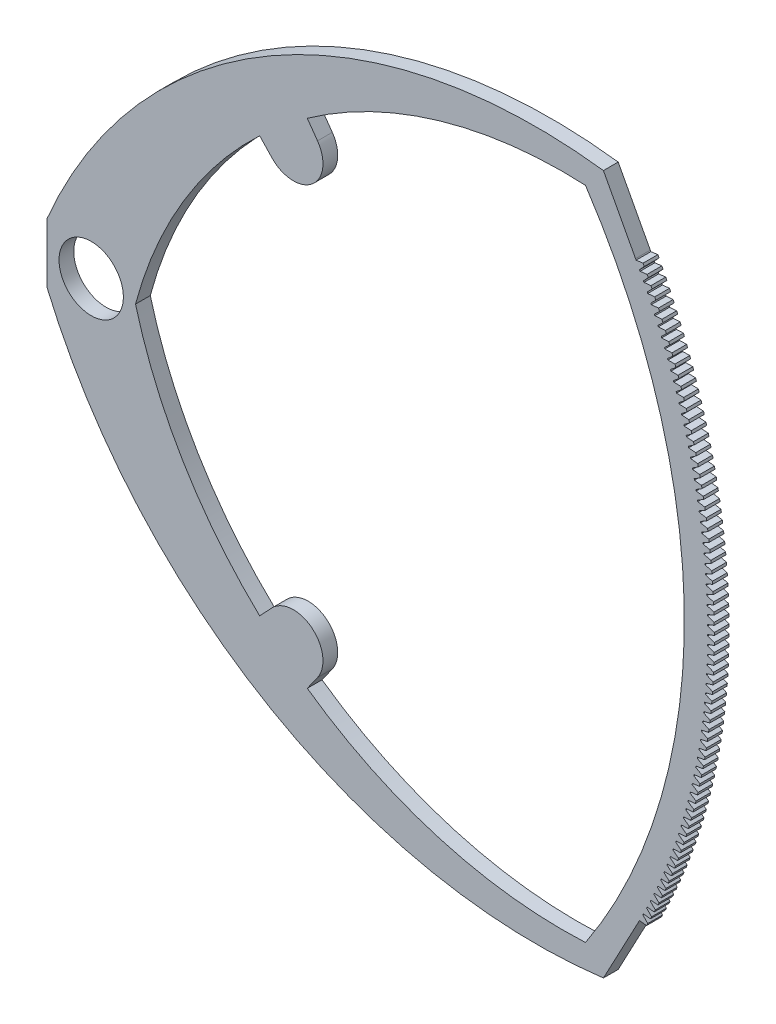
SolidWorks part; units mm, degrees
ref_plane "Plane1" through (0, 0, 0) normal (0, 0, 1) x (1, 0, 0)
ref_plane "Plane2" through (0, 0, 0) normal (0, 1, 0) x (1, 0, 0)
ref_plane "Plane3" through (0, 0, 0) normal (1, 0, 0) x (0, 0, -1)
sketch "Sketch3" plane through (0, 0, 0) normal (0, 0, 1) x (1, 0, 0)
  line L0 (0, 0) -> (305.6191, 0) construction
  line L2 (178.8854, 110) -> (173.446, 118.3912) construction
  line L5 (-15, -10) -> (-15, 10)
  line L12 (57.0436, 70.3911) -> (61.1578, 66.0237)
  line L13 (61.1578, 66.0237) -> (76.6329, 78.6934) construction
  line L14 (76.6329, 78.6934) -> (73.1635, 83.5887)
  line L15 (73.1635, 83.5887) -> (39.1944, 59.5144) construction
  line L16 (57.0436, 70.3911) -> (7.8883, 24.0861) construction
  line L17 (76.6329, -78.6934) -> (73.1635, -83.5887)
  line L18 (57.0436, -70.3911) -> (61.1578, -66.0237)
  line L19 (210.9931, 1.7084) -> (208.735, 2.4997)
  line L20 (208.75, 0) -> (210.9984, 0.8184)
  line L21 (209.9795, 2.9321) -> (0, 0) construction
  line L22 (208.7297, 2.9146) -> (210.9664, 3.7643)
  line L23 (210.9487, 4.6541) -> (208.6798, 5.4139)
  line L24 (208.6686, 5.8286) -> (210.8933, 6.7095)
  line L25 (210.8631, 7.599) -> (208.5839, 8.327)
  line L26 (208.5669, 8.7415) -> (210.7791, 9.6533)
  line L27 (210.7365, 10.5423) -> (208.4473, 11.2385)
  line L28 (208.4245, 11.6527) -> (210.6237, 12.5953)
  line L29 (210.5687, 13.4836) -> (208.27, 14.1477)
  line L30 (208.2415, 14.5617) -> (210.4273, 15.5349)
  line L31 (210.3599, 16.4223) -> (208.0522, 17.0543)
  line L32 (208.0179, 17.4677) -> (210.1899, 18.4714)
  line L33 (210.1102, 19.3578) -> (207.7938, 19.9575)
  line L34 (207.7537, 20.3704) -> (209.9115, 21.4043)
  line L35 (209.8194, 22.2895) -> (207.4949, 22.8568)
  line L36 (207.4491, 23.2691) -> (209.5922, 24.333)
  line L37 (209.4877, 25.2169) -> (207.1555, 25.7516)
  line L38 (207.1039, 26.1633) -> (209.2321, 27.257)
  line L39 (209.1152, 28.1393) -> (206.7758, 28.6415)
  line L40 (206.7185, 29.0524) -> (208.8311, 30.1757)
  line L41 (208.702, 31.0563) -> (206.3557, 31.5257)
  line L42 (206.2927, 31.9358) -> (208.3894, 33.0885)
  line L43 (208.248, 33.9672) -> (205.8955, 34.4038)
  line L44 (205.8267, 34.813) -> (207.9071, 35.9948)
  line L45 (207.7534, 36.8715) -> (205.395, 37.2752)
  line L46 (205.3205, 37.6834) -> (207.3843, 38.8942)
  line L47 (207.2184, 39.7686) -> (204.8546, 40.1393)
  line L48 (204.7744, 40.5464) -> (206.821, 41.7859)
  line L49 (206.6429, 42.6579) -> (204.2742, 42.9956)
  line L50 (204.1883, 43.4016) -> (206.2174, 44.6695)
  line L51 (206.0272, 45.539) -> (203.6539, 45.8436)
  line L52 (203.5624, 46.2482) -> (205.5737, 47.5444)
  line L53 (205.3713, 48.4111) -> (202.994, 48.6825)
  line L54 (202.8969, 49.0859) -> (204.8898, 50.41)
  line L55 (204.6753, 51.2738) -> (202.2945, 51.512)
  line L56 (202.1917, 51.914) -> (204.166, 53.2658)
  line L57 (203.9395, 54.1265) -> (201.5556, 54.3315)
  line L58 (201.4472, 54.732) -> (203.4024, 56.1112)
  line L59 (203.1639, 56.9687) -> (200.7773, 57.1403)
  line L60 (200.6634, 57.5393) -> (202.5991, 58.9457)
  line L61 (202.3487, 59.7998) -> (199.96, 59.9381)
  line L62 (199.8404, 60.3354) -> (201.7564, 61.7687)
  line L63 (201.494, 62.6192) -> (199.1036, 62.7241)
  line L64 (198.9786, 63.1197) -> (200.8743, 64.5796)
  line L65 (200.6001, 65.4263) -> (198.2084, 65.4979)
  line L66 (198.0779, 65.8917) -> (199.953, 67.378)
  line L67 (199.667, 68.2208) -> (197.2746, 68.2589)
  line L68 (197.1386, 68.6509) -> (198.9928, 70.1632)
  line L69 (198.6951, 71.0019) -> (196.3024, 71.0067)
  line L70 (196.1608, 71.3967) -> (197.9938, 72.9347)
  line L71 (197.6844, 73.7692) -> (195.2918, 73.7406)
  line L72 (195.1449, 74.1286) -> (196.9561, 75.692)
  line L73 (196.6351, 76.5221) -> (194.2432, 76.4601)
  line L74 (194.0908, 76.846) -> (195.8801, 78.4346)
  line L75 (195.5475, 79.2601) -> (193.1567, 79.1647)
  line L76 (192.999, 79.5484) -> (194.7659, 81.1619)
  line L77 (194.4218, 81.9827) -> (192.0326, 81.8539)
  line L78 (191.8695, 82.2354) -> (193.6137, 83.8733)
  line L79 (193.2582, 84.6892) -> (190.871, 84.5271)
  line L80 (190.7026, 84.9063) -> (192.4238, 86.5684)
  line L81 (192.0569, 87.3793) -> (189.6722, 87.1838)
  line L82 (189.4985, 87.5606) -> (191.1963, 89.2466)
  line L83 (190.8182, 90.0523) -> (188.4364, 89.8235)
  line L84 (188.2575, 90.1979) -> (189.9316, 91.9074)
  line L85 (189.5423, 92.7078) -> (187.1639, 92.4458)
  line L86 (186.9798, 92.8176) -> (188.6299, 94.5503)
  line L87 (188.2294, 95.3451) -> (185.855, 95.05)
  line L88 (185.6657, 95.4192) -> (187.2914, 97.1748)
  line L89 (186.8798, 97.9639) -> (184.5097, 97.6356)
  line L91 (210.9964, -1.2377) -> (208.7496, -0.4149)
  line L92 (208.7297, -2.9146) -> (210.9893, -2.1277)
  line L93 (210.9585, -4.1836) -> (208.7234, -3.3295)
  line L94 (208.6686, -5.8286) -> (210.939, -5.0734)
  line L95 (210.8795, -7.1286) -> (208.6566, -6.2434)
  line L96 (208.5669, -8.7415) -> (210.8476, -8.0181)
  line L97 (210.7595, -10.0723) -> (208.5491, -9.1561)
  line L98 (208.4245, -11.6527) -> (210.7151, -10.9612)
  line L99 (210.5983, -13.0139) -> (208.4009, -12.067)
  line L100 (208.2415, -14.5617) -> (210.5415, -13.9021)
  line L101 (210.3961, -15.9531) -> (208.2121, -14.9755)
  line L102 (208.0179, -17.4677) -> (210.3269, -16.8404)
  line L103 (210.1528, -18.8891) -> (207.9828, -17.8812)
  line L104 (207.7537, -20.3704) -> (210.0713, -19.7754)
  line L105 (209.8686, -21.8215) -> (207.7128, -20.7833)
  line L106 (207.4491, -23.2691) -> (209.7747, -22.7065)
  line L107 (209.5435, -24.7496) -> (207.4024, -23.6814)
  line L108 (207.1039, -26.1633) -> (209.4372, -25.6332)
  line L109 (209.1775, -27.6728) -> (207.0515, -26.5749)
  line L110 (206.7185, -29.0524) -> (209.0589, -28.5549)
  line L111 (208.7707, -30.5907) -> (206.6603, -29.4632)
  line L112 (206.2927, -31.9358) -> (208.6398, -31.471)
  line L113 (208.3232, -33.5026) -> (206.2288, -32.3458)
  line L114 (205.8267, -34.813) -> (208.1801, -34.381)
  line L115 (207.8352, -36.408) -> (205.7571, -35.222)
  line L116 (205.3205, -37.6834) -> (207.6797, -37.2843)
  line L117 (207.3066, -39.3063) -> (205.2452, -38.0914)
  line L118 (204.7744, -40.5464) -> (207.1389, -40.1804)
  line L119 (206.7376, -42.1969) -> (204.6934, -40.9534)
  line L120 (204.1883, -43.4016) -> (206.5577, -43.0686)
  line L121 (206.1283, -45.0793) -> (204.1016, -43.8073)
  line L122 (203.5624, -46.2482) -> (205.9363, -45.9484)
  line L123 (205.4788, -47.9529) -> (203.4701, -46.6528)
  line L124 (202.8969, -49.0859) -> (205.2747, -48.8192)
  line L125 (204.7892, -50.8172) -> (202.7989, -49.4891)
  line L126 (202.1917, -51.914) -> (204.573, -51.6805)
  line L127 (204.0597, -53.6715) -> (202.0882, -52.3158)
  line L128 (201.4472, -54.732) -> (203.8315, -54.5318)
  line L129 (203.2905, -56.5154) -> (201.338, -55.1323)
  line L130 (200.6634, -57.5393) -> (203.0503, -57.3724)
  line L131 (202.4816, -59.3483) -> (200.5486, -57.938)
  line L132 (199.8404, -60.3354) -> (202.2294, -60.2018)
  line L133 (201.6332, -62.1696) -> (199.7201, -60.7325)
  line L134 (198.9786, -63.1197) -> (201.3692, -63.0195)
  line L135 (200.7455, -64.9787) -> (198.8527, -63.5151)
  line L136 (198.0779, -65.8917) -> (200.4696, -65.8249)
  line L137 (199.8187, -67.7753) -> (197.9465, -66.2853)
  line L138 (197.1386, -68.6509) -> (199.531, -68.6175)
  line L139 (198.8529, -70.5586) -> (197.0017, -69.0426)
  line L140 (196.1608, -71.3967) -> (198.5535, -71.3967)
  line L141 (197.8484, -73.3281) -> (196.0185, -71.7865)
  line L142 (195.1449, -74.1286) -> (197.5373, -74.162)
  line L143 (196.8053, -76.0833) -> (194.9971, -74.5163)
  line L144 (194.0908, -76.846) -> (196.4826, -76.9128)
  line L145 (195.7238, -78.8238) -> (193.9377, -77.2316)
  line L146 (192.999, -79.5484) -> (195.3896, -79.6486)
  line L147 (194.6042, -81.5488) -> (192.8405, -79.9319)
  line L148 (191.8695, -82.2354) -> (194.2585, -82.3689)
  line L149 (193.4466, -84.258) -> (191.7057, -82.6166)
  line L150 (190.7026, -84.9063) -> (193.0895, -85.0732)
  line L151 (192.2513, -86.9507) -> (190.5335, -85.2851)
  line L152 (189.4985, -87.5606) -> (191.8829, -87.7608)
  line L153 (191.0186, -89.6265) -> (189.3241, -87.9371)
  line L154 (188.2575, -90.1979) -> (190.6388, -90.4314)
  line L155 (189.7486, -92.2848) -> (188.0779, -90.5719)
  line L156 (186.9798, -92.8176) -> (189.3576, -93.0843)
  line L157 (188.4416, -94.9251) -> (186.795, -93.1891)
  line L158 (185.6657, -95.4192) -> (188.0395, -95.7191)
  line L159 (173.446, 118.3912) -> (184.3153, 98.0022)
  line L160 (185.6657, -95.4192) -> (173.446, -118.3912)
  arc A1 (205.9994, 45.6647) -> (210.4201, -15.6324) centre (0, 0) cw construction
  arc A2 (178.8854, 110) -> (178.8854, -110) centre (0, 0) cw construction
  circle A3 centre (0, 0) radius 10.9
  circle A4 centre (100, 0) radius 70 construction
  arc A5 (15, 0) -> (178.8854, 110) centre (159.8968, -38.7933) cw construction
  arc A6 (-15, 10) -> (173.446, 118.3912) centre (150.758, -60.1732) cw
  arc A7 (-15, -10) -> (173.446, -118.3912) centre (150.758, 60.1732) ccw
  arc A9 (15, 0) -> (57.0436, 70.3911) centre (159.8968, -38.7933) cw
  arc A11 (76.6329, 78.6934) -> (61.1578, 66.0237) centre (68.4543, 72.8972) cw
  arc A12 (100, 0) -> (48.0915, 87.6767) centre (0, 0) ccw construction
  arc A14 (76.6329, -78.6934) -> (61.1578, -66.0237) centre (68.4543, -72.8972) ccw
  arc A15 (15, 0) -> (57.0436, -70.3911) centre (159.8968, 38.7933) ccw
  arc A16 (208.067, -16.8729) -> (203.5312, 46.3854) centre (0, 0) ccw construction
  arc A17 (208.7297, 2.9146) -> (208.735, 2.4997) centre (0, 0) cw
  arc A18 (210.9984, 0.8184) -> (210.9931, 1.7084) centre (0, 0) ccw
  arc A19 (210.9664, 3.7643) -> (210.9487, 4.6541) centre (0, 0) ccw
  arc A20 (208.6686, 5.8286) -> (208.6798, 5.4139) centre (0, 0) cw
  arc A21 (210.8933, 6.7095) -> (210.8631, 7.599) centre (0, 0) ccw
  arc A22 (208.5669, 8.7415) -> (208.5839, 8.327) centre (0, 0) cw
  arc A23 (210.7791, 9.6533) -> (210.7365, 10.5423) centre (0, 0) ccw
  arc A24 (208.4245, 11.6527) -> (208.4473, 11.2385) centre (0, 0) cw
  arc A25 (210.6237, 12.5953) -> (210.5687, 13.4836) centre (0, 0) ccw
  arc A26 (208.2415, 14.5617) -> (208.27, 14.1477) centre (0, 0) cw
  arc A27 (210.4273, 15.5349) -> (210.3599, 16.4223) centre (0, 0) ccw
  arc A28 (208.0179, 17.4677) -> (208.0522, 17.0543) centre (0, 0) cw
  arc A29 (210.1899, 18.4714) -> (210.1102, 19.3578) centre (0, 0) ccw
  arc A30 (207.7537, 20.3704) -> (207.7938, 19.9575) centre (0, 0) cw
  arc A31 (209.9115, 21.4043) -> (209.8194, 22.2895) centre (0, 0) ccw
  arc A32 (207.4491, 23.2691) -> (207.4949, 22.8568) centre (0, 0) cw
  arc A33 (209.5922, 24.333) -> (209.4877, 25.2169) centre (0, 0) ccw
  arc A34 (207.1039, 26.1633) -> (207.1555, 25.7516) centre (0, 0) cw
  arc A35 (209.2321, 27.257) -> (209.1152, 28.1393) centre (0, 0) ccw
  arc A36 (206.7185, 29.0524) -> (206.7758, 28.6415) centre (0, 0) cw
  arc A37 (208.8311, 30.1757) -> (208.702, 31.0563) centre (0, 0) ccw
  arc A38 (206.2927, 31.9358) -> (206.3557, 31.5257) centre (0, 0) cw
  arc A39 (208.3894, 33.0885) -> (208.248, 33.9672) centre (0, 0) ccw
  arc A40 (205.8267, 34.813) -> (205.8955, 34.4038) centre (0, 0) cw
  arc A41 (207.9071, 35.9948) -> (207.7534, 36.8715) centre (0, 0) ccw
  arc A42 (205.3205, 37.6834) -> (205.395, 37.2752) centre (0, 0) cw
  arc A43 (207.3843, 38.8942) -> (207.2184, 39.7686) centre (0, 0) ccw
  arc A44 (204.7744, 40.5464) -> (204.8546, 40.1393) centre (0, 0) cw
  arc A45 (206.821, 41.7859) -> (206.6429, 42.6579) centre (0, 0) ccw
  arc A46 (204.1883, 43.4016) -> (204.2742, 42.9956) centre (0, 0) cw
  arc A47 (206.2174, 44.6695) -> (206.0272, 45.539) centre (0, 0) ccw
  arc A48 (203.5624, 46.2482) -> (203.6539, 45.8436) centre (0, 0) cw
  arc A49 (205.5737, 47.5444) -> (205.3713, 48.4111) centre (0, 0) ccw
  arc A50 (202.8969, 49.0859) -> (202.994, 48.6825) centre (0, 0) cw
  arc A51 (204.8898, 50.41) -> (204.6753, 51.2738) centre (0, 0) ccw
  arc A52 (202.1917, 51.914) -> (202.2945, 51.512) centre (0, 0) cw
  arc A53 (204.166, 53.2658) -> (203.9395, 54.1265) centre (0, 0) ccw
  arc A54 (201.4472, 54.732) -> (201.5556, 54.3315) centre (0, 0) cw
  arc A55 (203.4024, 56.1112) -> (203.1639, 56.9687) centre (0, 0) ccw
  arc A56 (200.6634, 57.5393) -> (200.7773, 57.1403) centre (0, 0) cw
  arc A57 (202.5991, 58.9457) -> (202.3487, 59.7998) centre (0, 0) ccw
  arc A58 (199.8404, 60.3354) -> (199.96, 59.9381) centre (0, 0) cw
  arc A59 (201.7564, 61.7687) -> (201.494, 62.6192) centre (0, 0) ccw
  arc A60 (198.9786, 63.1197) -> (199.1036, 62.7241) centre (0, 0) cw
  arc A61 (200.8743, 64.5796) -> (200.6001, 65.4263) centre (0, 0) ccw
  arc A62 (198.0779, 65.8917) -> (198.2084, 65.4979) centre (0, 0) cw
  arc A63 (199.953, 67.378) -> (199.667, 68.2208) centre (0, 0) ccw
  arc A64 (197.1386, 68.6509) -> (197.2746, 68.2589) centre (0, 0) cw
  arc A65 (198.9928, 70.1632) -> (198.6951, 71.0019) centre (0, 0) ccw
  arc A66 (196.1608, 71.3967) -> (196.3024, 71.0067) centre (0, 0) cw
  arc A67 (197.9938, 72.9347) -> (197.6844, 73.7692) centre (0, 0) ccw
  arc A68 (195.1449, 74.1286) -> (195.2918, 73.7406) centre (0, 0) cw
  arc A69 (196.9561, 75.692) -> (196.6351, 76.5221) centre (0, 0) ccw
  arc A70 (194.0908, 76.846) -> (194.2432, 76.4601) centre (0, 0) cw
  arc A71 (195.8801, 78.4346) -> (195.5475, 79.2601) centre (0, 0) ccw
  arc A72 (192.999, 79.5484) -> (193.1567, 79.1647) centre (0, 0) cw
  arc A73 (194.7659, 81.1619) -> (194.4218, 81.9827) centre (0, 0) ccw
  arc A74 (191.8695, 82.2354) -> (192.0326, 81.8539) centre (0, 0) cw
  arc A75 (193.6137, 83.8733) -> (193.2582, 84.6892) centre (0, 0) ccw
  arc A76 (190.7026, 84.9063) -> (190.871, 84.5271) centre (0, 0) cw
  arc A77 (192.4238, 86.5684) -> (192.0569, 87.3793) centre (0, 0) ccw
  arc A78 (189.4985, 87.5606) -> (189.6722, 87.1838) centre (0, 0) cw
  arc A79 (191.1963, 89.2466) -> (190.8182, 90.0523) centre (0, 0) ccw
  arc A80 (188.2575, 90.1979) -> (188.4364, 89.8235) centre (0, 0) cw
  arc A81 (189.9316, 91.9074) -> (189.5423, 92.7078) centre (0, 0) ccw
  arc A82 (186.9798, 92.8176) -> (187.1639, 92.4458) centre (0, 0) cw
  arc A83 (188.6299, 94.5503) -> (188.2294, 95.3451) centre (0, 0) ccw
  arc A84 (185.6657, 95.4192) -> (185.855, 95.05) centre (0, 0) cw
  arc A85 (187.2914, 97.1748) -> (186.8798, 97.9639) centre (0, 0) ccw
  arc A86 (184.3153, 98.0022) -> (184.5097, 97.6356) centre (0, 0) cw
  arc A87 (208.75, 0) -> (208.7496, -0.4149) centre (0, 0) cw
  arc A88 (210.9893, -2.1277) -> (210.9964, -1.2377) centre (0, 0) ccw
  arc A89 (208.7297, -2.9146) -> (208.7234, -3.3295) centre (0, 0) cw
  arc A90 (210.939, -5.0734) -> (210.9585, -4.1836) centre (0, 0) ccw
  arc A91 (208.6686, -5.8286) -> (208.6566, -6.2434) centre (0, 0) cw
  arc A92 (210.8476, -8.0181) -> (210.8795, -7.1286) centre (0, 0) ccw
  arc A93 (208.5669, -8.7415) -> (208.5491, -9.1561) centre (0, 0) cw
  arc A94 (210.7151, -10.9612) -> (210.7595, -10.0723) centre (0, 0) ccw
  arc A95 (208.4245, -11.6527) -> (208.4009, -12.067) centre (0, 0) cw
  arc A96 (210.5415, -13.9021) -> (210.5983, -13.0139) centre (0, 0) ccw
  arc A97 (208.2415, -14.5617) -> (208.2121, -14.9755) centre (0, 0) cw
  arc A98 (210.3269, -16.8404) -> (210.3961, -15.9531) centre (0, 0) ccw
  arc A99 (208.0179, -17.4677) -> (207.9828, -17.8812) centre (0, 0) cw
  arc A100 (210.0713, -19.7754) -> (210.1528, -18.8891) centre (0, 0) ccw
  arc A101 (207.7537, -20.3704) -> (207.7128, -20.7833) centre (0, 0) cw
  arc A102 (209.7747, -22.7065) -> (209.8686, -21.8215) centre (0, 0) ccw
  arc A103 (207.4491, -23.2691) -> (207.4024, -23.6814) centre (0, 0) cw
  arc A104 (209.4372, -25.6332) -> (209.5435, -24.7496) centre (0, 0) ccw
  arc A105 (207.1039, -26.1633) -> (207.0515, -26.5749) centre (0, 0) cw
  arc A106 (209.0589, -28.5549) -> (209.1775, -27.6728) centre (0, 0) ccw
  arc A107 (206.7185, -29.0524) -> (206.6603, -29.4632) centre (0, 0) cw
  arc A108 (208.6398, -31.471) -> (208.7707, -30.5907) centre (0, 0) ccw
  arc A109 (206.2927, -31.9358) -> (206.2288, -32.3458) centre (0, 0) cw
  arc A110 (208.1801, -34.381) -> (208.3232, -33.5026) centre (0, 0) ccw
  arc A111 (205.8267, -34.813) -> (205.7571, -35.222) centre (0, 0) cw
  arc A112 (207.6797, -37.2843) -> (207.8352, -36.408) centre (0, 0) ccw
  arc A113 (205.3205, -37.6834) -> (205.2452, -38.0914) centre (0, 0) cw
  arc A114 (207.1389, -40.1804) -> (207.3066, -39.3063) centre (0, 0) ccw
  arc A115 (204.7744, -40.5464) -> (204.6934, -40.9534) centre (0, 0) cw
  arc A116 (206.5577, -43.0686) -> (206.7376, -42.1969) centre (0, 0) ccw
  arc A117 (204.1883, -43.4016) -> (204.1016, -43.8073) centre (0, 0) cw
  arc A118 (205.9363, -45.9484) -> (206.1283, -45.0793) centre (0, 0) ccw
  arc A119 (203.5624, -46.2482) -> (203.4701, -46.6528) centre (0, 0) cw
  arc A120 (205.2747, -48.8192) -> (205.4788, -47.9529) centre (0, 0) ccw
  arc A121 (202.8969, -49.0859) -> (202.7989, -49.4891) centre (0, 0) cw
  arc A122 (204.573, -51.6805) -> (204.7892, -50.8172) centre (0, 0) ccw
  arc A123 (202.1917, -51.914) -> (202.0882, -52.3158) centre (0, 0) cw
  arc A124 (203.8315, -54.5318) -> (204.0597, -53.6715) centre (0, 0) ccw
  arc A125 (201.4472, -54.732) -> (201.338, -55.1323) centre (0, 0) cw
  arc A126 (203.0503, -57.3724) -> (203.2905, -56.5154) centre (0, 0) ccw
  arc A127 (200.6634, -57.5393) -> (200.5486, -57.938) centre (0, 0) cw
  arc A128 (202.2294, -60.2018) -> (202.4816, -59.3483) centre (0, 0) ccw
  arc A129 (199.8404, -60.3354) -> (199.7201, -60.7325) centre (0, 0) cw
  arc A130 (201.3692, -63.0195) -> (201.6332, -62.1696) centre (0, 0) ccw
  arc A131 (198.9786, -63.1197) -> (198.8527, -63.5151) centre (0, 0) cw
  arc A132 (200.4696, -65.8249) -> (200.7455, -64.9787) centre (0, 0) ccw
  arc A133 (198.0779, -65.8917) -> (197.9465, -66.2853) centre (0, 0) cw
  arc A134 (199.531, -68.6175) -> (199.8187, -67.7753) centre (0, 0) ccw
  arc A135 (197.1386, -68.6509) -> (197.0017, -69.0426) centre (0, 0) cw
  arc A136 (198.5535, -71.3967) -> (198.8529, -70.5586) centre (0, 0) ccw
  arc A137 (196.1608, -71.3967) -> (196.0185, -71.7865) centre (0, 0) cw
  arc A138 (197.5373, -74.162) -> (197.8484, -73.3281) centre (0, 0) ccw
  arc A139 (195.1449, -74.1286) -> (194.9971, -74.5163) centre (0, 0) cw
  arc A140 (196.4826, -76.9128) -> (196.8053, -76.0833) centre (0, 0) ccw
  arc A141 (194.0908, -76.846) -> (193.9377, -77.2316) centre (0, 0) cw
  arc A142 (195.3896, -79.6486) -> (195.7238, -78.8238) centre (0, 0) ccw
  arc A143 (192.999, -79.5484) -> (192.8405, -79.9319) centre (0, 0) cw
  arc A144 (194.2585, -82.3689) -> (194.6042, -81.5488) centre (0, 0) ccw
  arc A145 (191.8695, -82.2354) -> (191.7057, -82.6166) centre (0, 0) cw
  arc A146 (193.0895, -85.0732) -> (193.4466, -84.258) centre (0, 0) ccw
  arc A147 (190.7026, -84.9063) -> (190.5335, -85.2851) centre (0, 0) cw
  arc A148 (191.8829, -87.7608) -> (192.2513, -86.9507) centre (0, 0) ccw
  arc A149 (189.4985, -87.5606) -> (189.3241, -87.9371) centre (0, 0) cw
  arc A150 (190.6388, -90.4314) -> (191.0186, -89.6265) centre (0, 0) ccw
  arc A151 (188.2575, -90.1979) -> (188.0779, -90.5719) centre (0, 0) cw
  arc A152 (189.3576, -93.0843) -> (189.7486, -92.2848) centre (0, 0) ccw
  arc A153 (186.9798, -92.8176) -> (186.795, -93.1891) centre (0, 0) cw
  arc A154 (188.0395, -95.7191) -> (188.4416, -94.9251) centre (0, 0) ccw
  arc A155 (167.38, 111.02) -> (167.38, -111.02) centre (0, 0) cw
  arc A156 (15, 0) -> (178.8854, -110) centre (159.8968, 38.7933) ccw construction
  arc A157 (73.1635, 83.5887) -> (167.38, 111.02) centre (159.8968, -38.7933) cw
  arc A158 (73.1635, -83.5887) -> (167.38, -111.02) centre (159.8968, 38.7933) ccw
  point P9 (209.9995, 0.4548)
  point P41 (209.9899, 2.0599)
  point P218 (0, 0)
  point P355 (0, 0)
  dimension "D1" = 10
  dimension "D2" = 140
  dimension "D4" = 15
  dimension "D7" = 20
  dimension "D9" = 150
  dimension "D10" = 180
  dimension "D13" = 1.25
  dimension "D14" = 1
  dimension "D15" = 210
  dimension "D16" = 0.8
  dimension "D21" = 21.8
  dimension "D3" = 100
  dimension "D5" = 15
  dimension "D6" = 20
  dimension "D8" = 6
  dimension "D12" = 20
  dimension "D17" = 0.89
  dimension "D19" = 110
  dimension "D20" = 35
  dimension "D18" = 35
extrude "Boss-Extrude2" add sketch "Sketch3" along normal blind 5
